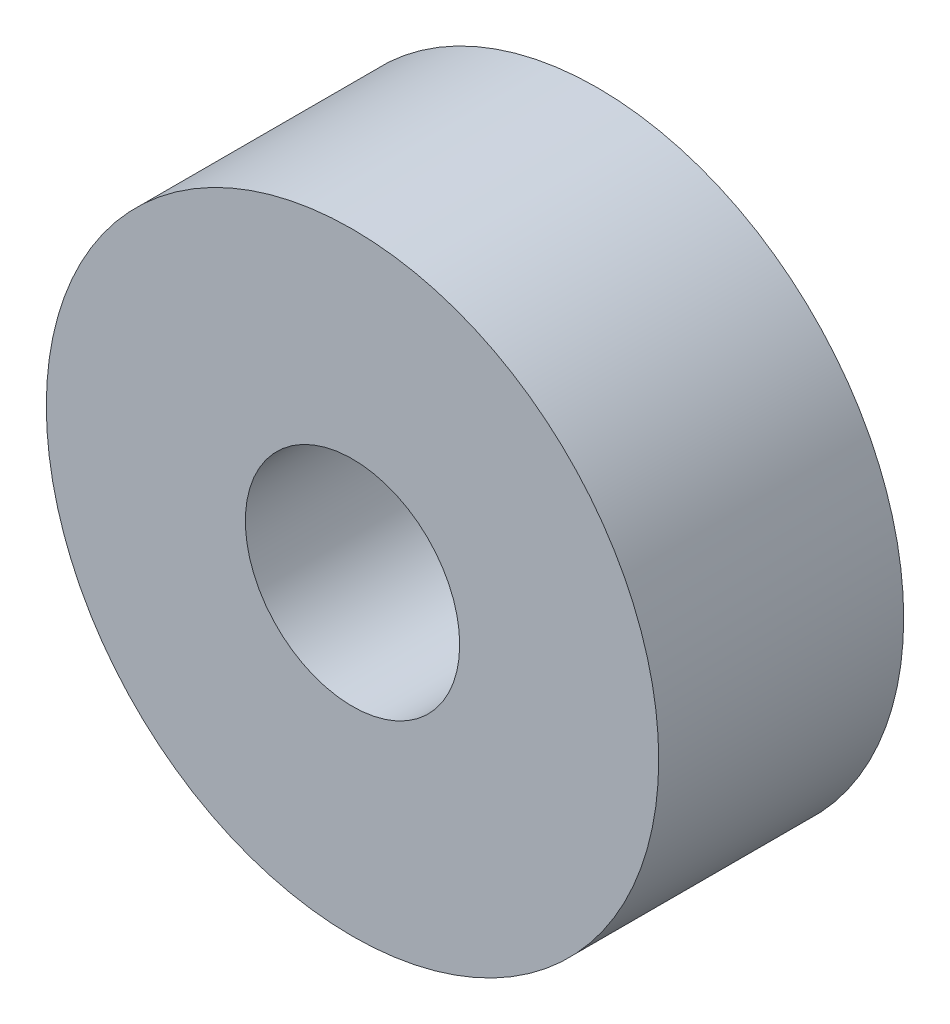
SolidWorks part; units mm, degrees
ref_plane "Front Plane" through (0, 0, 0) normal (0, 0, 1) x (1, 0, 0)
ref_plane "Top Plane" through (0, 0, 0) normal (0, 1, 0) x (1, 0, 0)
ref_plane "Right Plane" through (0, 0, 0) normal (1, 0, 0) x (0, 0, -1)
sketch "Sketch1" plane through (0, 0, 0) normal (0, 0, 1) x (1, 0, 0)
  circle A0 centre (0, 0) radius 25.4
  circle A1 centre (0, 0) radius 8.89
  dimension "D1" = 50.8
  dimension "D2" = 17.78
extrude "Boss-Extrude1" add sketch "Sketch1" along normal blind 20.32
